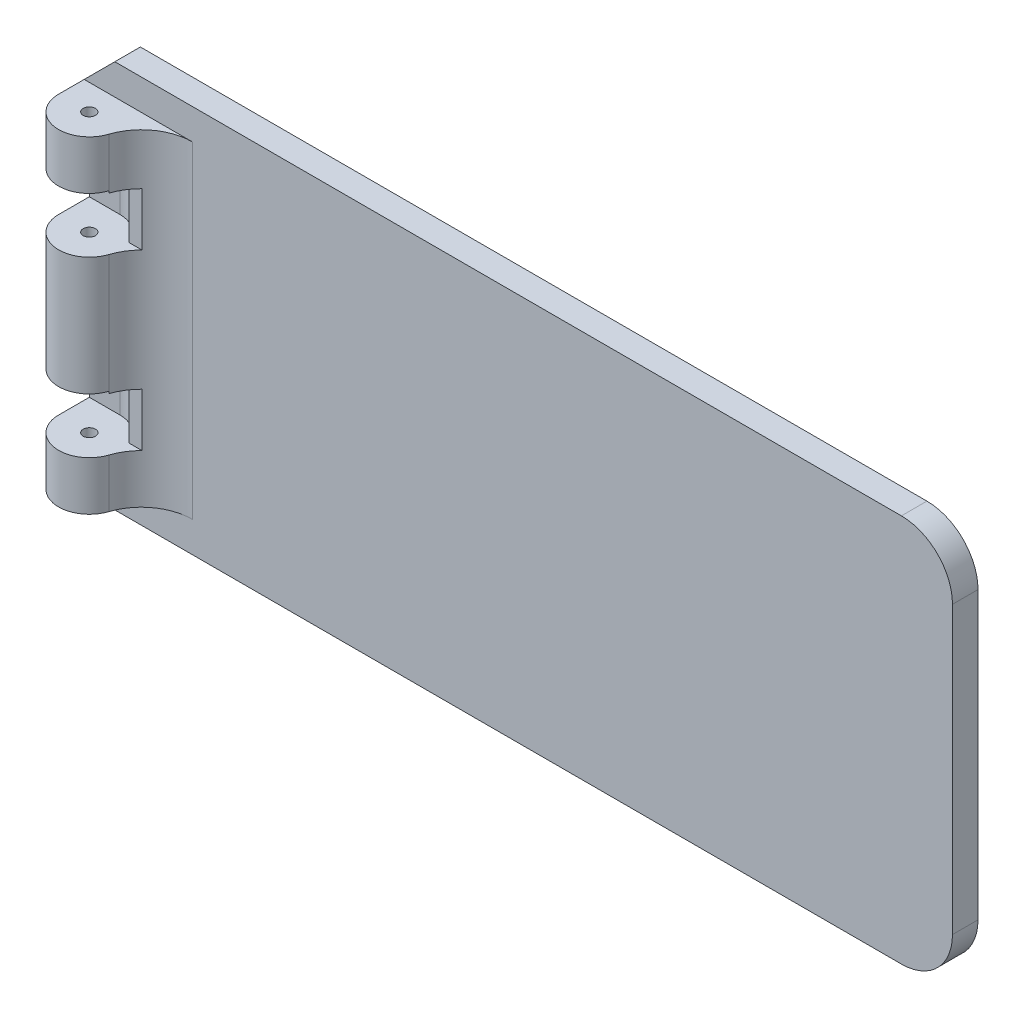
SolidWorks part; units mm, degrees
ref_plane "Front Plane" through (0, 0, 0) normal (0, 0, 1) x (1, 0, 0)
ref_plane "Top Plane" through (0, 0, 0) normal (0, 1, 0) x (1, 0, 0)
ref_plane "Right Plane" through (0, 0, 0) normal (1, 0, 0) x (0, 0, -1)
sketch "Sketch1" plane through (0, 0, 0) normal (0, 1, 0) x (1, 0, 0)
  line L0 (3, 0) -> (3, -11.9691) construction
  line L1 (0, 0) -> (85, 0)
  line L2 (0, 0) -> (0, -2.5)
  line L3 (0, -2.5) -> (85, -2.5)
  line L4 (85, 0) -> (85, -2.5)
  line L5 (0, -5) -> (0, -2.5)
  line L6 (0, -2.5) -> (3, -2.5)
  line L7 (3, -2.5) -> (0, -5)
  circle A0 centre (3, -5) radius 0.6
  circle A1 centre (3, -5) radius 3
  dimension "D3" = 3
  dimension "D1" = 85
  dimension "D2" = 2.5
  dimension "D4" = 5
extrude "Boss-Extrude1" add sketch "Sketch1" along normal blind 38 contours L1 L0 A1 L3 L4 | L0 L1 L2 L3 A1 | A1 L3 L5 | L0 L7 A1 A0 | L3 L0 A0 A1 | L6 A1 L7 | L0 A1 L6 | A1 L0 L3
fillet "Fillet1" radius 5 1 edges at (4.6583, 19, 2.5)
sketch "Sketch3" plane through (0, 0, 0) normal (0, 0, -1) x (-1, 0, 0)
  line L0 (0, 19) -> (-85, 19) construction
  line L1 (0, 38) -> (0, 0) construction
  line L2 (-85, 38) -> (-85, 0) construction
  line L3 (0, 10.5) -> (-26.2876, 10.5) construction
  line L4 (0, 27.5) -> (-26.2876, 27.5) construction
  point P10 (-13.1438, 10.5)
  dimension "D1" = 8.5
  dimension "D2" = 8.5
ref_plane "Plane1" through (0, 10.5, 0) normal (0, 1, 0) x (1, 0, 0)
ref_plane "Plane2" through (0, 27.5, 0) normal (0, 1, 0) x (1, 0, 0)
sketch "Sketch4" plane through (0, 27.5, 0) normal (0, 1, 0) x (1, 0, 0)
  line L0 (3, -2) -> (0, -2)
  line L1 (0, 0) -> (0, -5) construction
  line L2 (0, -2) -> (0, -5)
  circle A0 centre (3, -5) radius 3
extrude "Cut-Extrude2" cut sketch "Sketch4" against normal blind 2.7 and the other way blind 2.7 contours A0 | A0 L0 L2
sketch "Sketch5" plane through (0, 10.5, 0) normal (0, 1, 0) x (1, 0, 0)
  line L0 (3, -2) -> (0, -2)
  line L1 (0, 0) -> (0, -5) construction
  line L2 (0, -2) -> (0, -5)
  circle A0 centre (3, -5) radius 3
extrude "Cut-Extrude3" cut sketch "Sketch5" against normal blind 2.7 and the other way blind 2.7 contours A0 | A0 L0 L2
sketch "Sketch6" plane through (0, 38, 0) normal (0, 1, 0) x (1, 0, 0)
  line L0 (10.5993, -2.5) -> (85, -2.5) construction
  line L1 (13.7263, -2.5) -> (-2.0807, -2.5)
  line L2 (13.7263, -2.5) -> (13.7263, -9.7625)
  line L3 (13.7263, -9.7625) -> (-2.0807, -9.7625)
  line L4 (-2.0807, -2.5) -> (-2.0807, -9.7625)
extrude "Cut-Extrude4" cut sketch "Sketch6" against normal blind 3
sketch "Sketch7" plane through (0, 0, 0) normal (0, -1, 0) x (1, 0, 0)
  line L0 (10.5993, 2.5) -> (85, 2.5) construction
  line L1 (25.4715, 2.5) -> (-2.727, 2.5)
  line L2 (25.4715, 2.5) -> (25.4715, 10.227)
  line L3 (25.4715, 10.227) -> (-2.727, 10.227)
  line L4 (-2.727, 2.5) -> (-2.727, 10.227)
extrude "Cut-Extrude5" cut sketch "Sketch7" against normal blind 3
chamfer "Chamfer1" distance 3 angle 45 2 edges at (0, 38, 1.25) (0, 0, 1.25)
fillet "Fillet2" radius 5 2 edges at (85, 0, 1.25) (85, 38, 1.25)
ref_plane "Plane3" through (0, 0, 5.9375) normal (0, 0, 1) x (1, 0, 0)
sketch "Sketch8" plane through (0, 0, 5.9375) normal (0, 0, 1) x (1, 0, 0)
  line L0 (5.8498, 7.8) -> (0, 7.8) construction
  line L1 (3.4833, 7.8) -> (10.3614, 7.8)
  line L2 (3.4833, 7.8) -> (3.4833, 13)
  line L3 (3.4833, 13) -> (10.3614, 13)
  line L4 (10.3614, 7.8) -> (10.3614, 13)
  line L5 (5.8498, 24.8) -> (0, 24.8) construction
  line L6 (3.4833, 24.8) -> (9.8838, 24.8)
  line L7 (3.4833, 24.8) -> (3.4833, 30)
  line L8 (3.4833, 30) -> (9.8838, 30)
  line L9 (9.8838, 24.8) -> (9.8838, 30)
extrude "Cut-Extrude6" cut sketch "Sketch8" against normal blind 2
